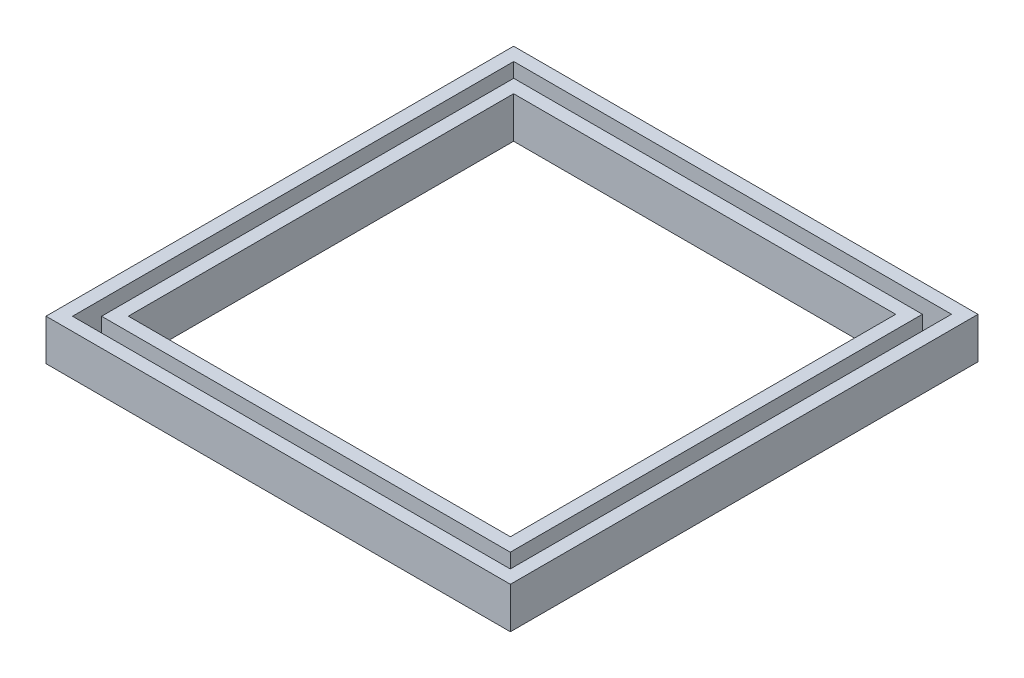
SolidWorks part; units mm, degrees
ref_plane "Front Plane" through (0, 0, 0) normal (0, 0, 1) x (1, 0, 0)
ref_plane "Top Plane" through (0, 0, 0) normal (0, 1, 0) x (1, 0, 0)
ref_plane "Right Plane" through (0, 0, 0) normal (1, 0, 0) x (0, 0, -1)
sketch "Sketch1" plane through (0, 0, 0) normal (0, 1, 0) x (1, 0, 0)
  line L0 (94.57, 95.37) -> (101.3, 95.37) construction
  line L1 (-94.57, -95.37) -> (94.57, -95.37)
  line L2 (-94.57, -95.37) -> (-94.57, 95.37)
  line L3 (-94.57, 95.37) -> (94.57, 95.37)
  line L4 (94.57, -95.37) -> (94.57, 95.37)
  line L5 (-94.57, -95.37) -> (94.57, 95.37) construction
  line L6 (-94.57, 95.37) -> (94.57, -95.37) construction
  line L7 (-101.3, -102.1) -> (101.3, -102.1)
  line L8 (-101.3, -102.1) -> (-101.3, 102.1)
  line L9 (-101.3, 102.1) -> (101.3, 102.1)
  line L10 (101.3, -102.1) -> (101.3, 102.1)
  line L11 (-101.3, -102.1) -> (101.3, 102.1) construction
  line L12 (-101.3, 102.1) -> (101.3, -102.1) construction
  line L13 (-88.41, -89.1579) -> (88.41, -89.1579)
  line L14 (-88.41, -89.1579) -> (-88.41, 89.1579)
  line L15 (-88.41, 89.1579) -> (88.41, 89.1579)
  line L16 (88.41, -89.1579) -> (88.41, 89.1579)
  line L17 (-88.41, -89.1579) -> (88.41, 89.1579) construction
  line L18 (-88.41, 89.1579) -> (88.41, -89.1579) construction
  line L19 (-107.46, -108.2079) -> (107.46, -108.2079)
  line L20 (-107.46, -108.2079) -> (-107.46, 108.2079)
  line L21 (-107.46, 108.2079) -> (107.46, 108.2079)
  line L22 (107.46, -108.2079) -> (107.46, 108.2079)
  line L23 (-107.46, -108.2079) -> (107.46, 108.2079) construction
  line L24 (-107.46, 108.2079) -> (107.46, -108.2079) construction
  point P0 (0, 0)
  point P6 (0, 0)
  point P11 (0, 0)
  point P16 (0, 0)
  point P21 (97.935, 95.37)
  dimension "D1" = 189.14
  dimension "D2" = 190.74
  dimension "D3" = 6.73
  dimension "D4" = 6.73
  dimension "D5" = 19.05
  dimension "D6" = 19.05
  dimension "D7" = 9.525
extrude "Boss-Extrude2" add sketch "Sketch1" along normal blind 19.05 contours L1 L4 L3 L2 L16 L13 L14 L15 | L19 L22 L21 L20 L10 L7 L8 L9
ref_plane "Plane1" through (0, 130, 0) normal (0, 1, 0) x (1, 0, 0)
sketch "Sketch2" plane through (0, 130, 0) normal (0, 1, 0) x (1, 0, 0)
  line L0 (-88.41, -89.1579) -> (-88.41, 89.1579) construction
  line L1 (-139.21, -139.9579) -> (139.21, -139.9579)
  line L2 (-139.21, -139.9579) -> (-139.21, 139.9579)
  line L3 (-139.21, 139.9579) -> (139.21, 139.9579)
  line L4 (139.21, -139.9579) -> (139.21, 139.9579)
  line L5 (-139.21, -139.9579) -> (139.21, 139.9579) construction
  line L6 (-139.21, 139.9579) -> (139.21, -139.9579) construction
  line L7 (-88.41, -89.1579) -> (88.41, -89.1579) construction
  line L9 (-158.26, -159.0079) -> (158.26, -159.0079)
  line L10 (-158.26, -159.0079) -> (-158.26, 159.0079)
  line L11 (-158.26, 159.0079) -> (158.26, 159.0079)
  line L12 (158.26, -159.0079) -> (158.26, 159.0079)
  line L13 (-158.26, -159.0079) -> (158.26, 159.0079) construction
  line L14 (-158.26, 159.0079) -> (158.26, -159.0079) construction
  point P0 (0, 0)
  point P10 (0, 0)
  dimension "D1" = 50.8
  dimension "D2" = 50.8
  dimension "D3" = 19.05
  dimension "D4" = 19.05
